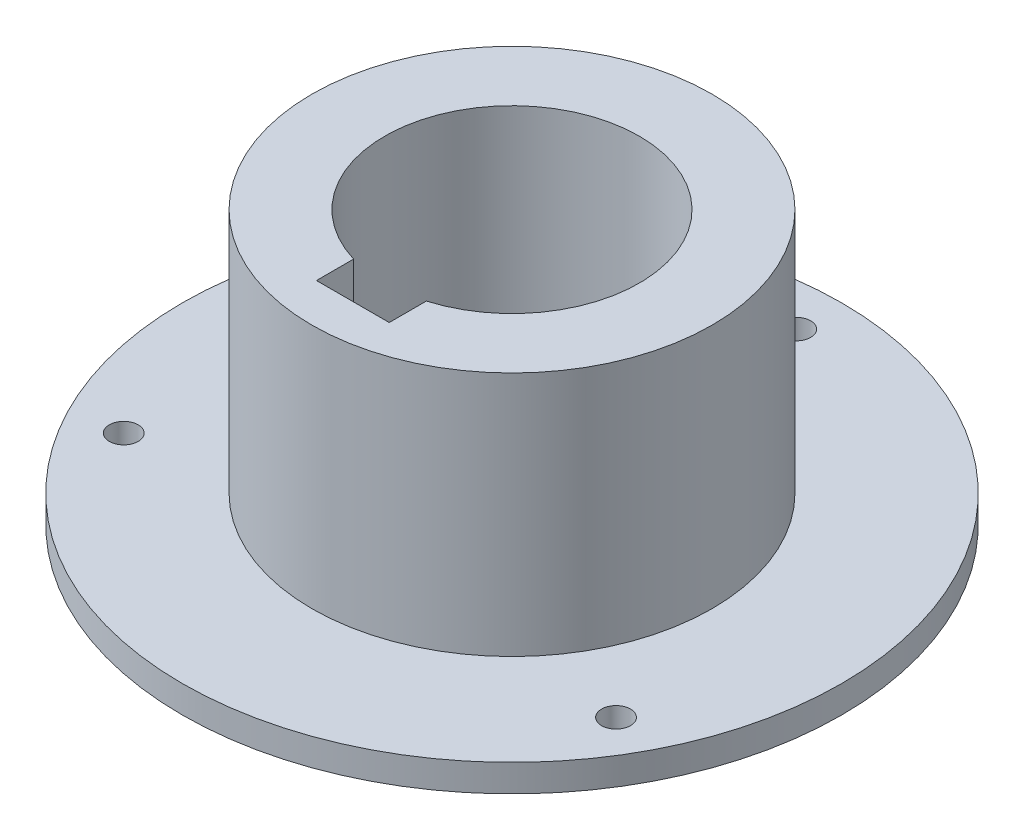
SolidWorks part; units mm, degrees
ref_plane "Front Plane" through (0, 0, 0) normal (0, 0, 1) x (1, 0, 0)
ref_plane "Top Plane" through (0, 0, 0) normal (0, 1, 0) x (1, 0, 0)
ref_plane "Right Plane" through (0, 0, 0) normal (1, 0, 0) x (0, 0, -1)
sketch "Sketch1" plane through (0, 0, 0) normal (0, 0, 1) x (1, 0, 0)
  line L3 (22, 30) -> (22, 3)
  line L4 (22, 3) -> (36.25, 3)
  line L5 (36.25, 3) -> (36.25, 0)
  line L10 (0, 0) -> (0, 11.4483)
  line L11 (19.25, 0) -> (36.25, 0)
  line L12 (19.25, -2) -> (19.25, 0)
  line L13 (19.25, -2) -> (14, -2)
  line L14 (14, -2) -> (14, 30)
  line L15 (14, 30) -> (22, 30)
revolve "Revolve1" add sketch "Sketch1" angle 360 about L10
sketch "Sketch2" plane through (0, 3, 0) normal (0, 1, 0) x (1, 0, 0)
  line L0 (0, 11.25) -> (0, 31.25)
  line L1 (0, 0) -> (0, 31.25)
hole_wizard "1/8 (0.125) Diameter Hole1" positions "Sketch3" profile "Sketch4" hole size "1/8" standard "ANSI Inch" end condition through all
sketch "Sketch3" plane through (0, 3, 0) normal (0, 1, 0) x (1, 0, 0)
  point P0 (0, 31.25)
sketch "Sketch4" plane through (0, 3, -31.25) normal (1, 0, 0) x (0, 0, 1)
  line L0 (0, 0) -> (0, 5)
  line L1 (0, 5) -> (1.5875, 5)
  line L2 (1.5875, 5) -> (1.5875, 0)
  line L5 (1.5875, 0) -> (0, 0)
  line L11 (0, -6.35) -> (0, 107.95) construction
  dimension "Thru Hole Dia." = 3.175
  dimension "Thru Hole Depth" = 5
pattern_circular "CirPattern1" count 3 every 120 about axis through (0, 0, 0) along (0, 1, 0) of "1/8 (0.125) Diameter Hole1"
sketch "Sketch7" plane through (0, 30, 0) normal (0, 1, 0) x (1, 0, 0)
  line L1 (0, -17.5) -> (4, -17.5)
  line L2 (0, -17.5) -> (-4, -17.5)
  line L3 (-4, -17.5) -> (-4, -12.9195)
  line L4 (-4, -12.9195) -> (4, -12.9195)
  line L5 (4, -12.9195) -> (4, -17.5)
extrude "Cut-Extrude2" cut sketch "Sketch7" against normal through all
